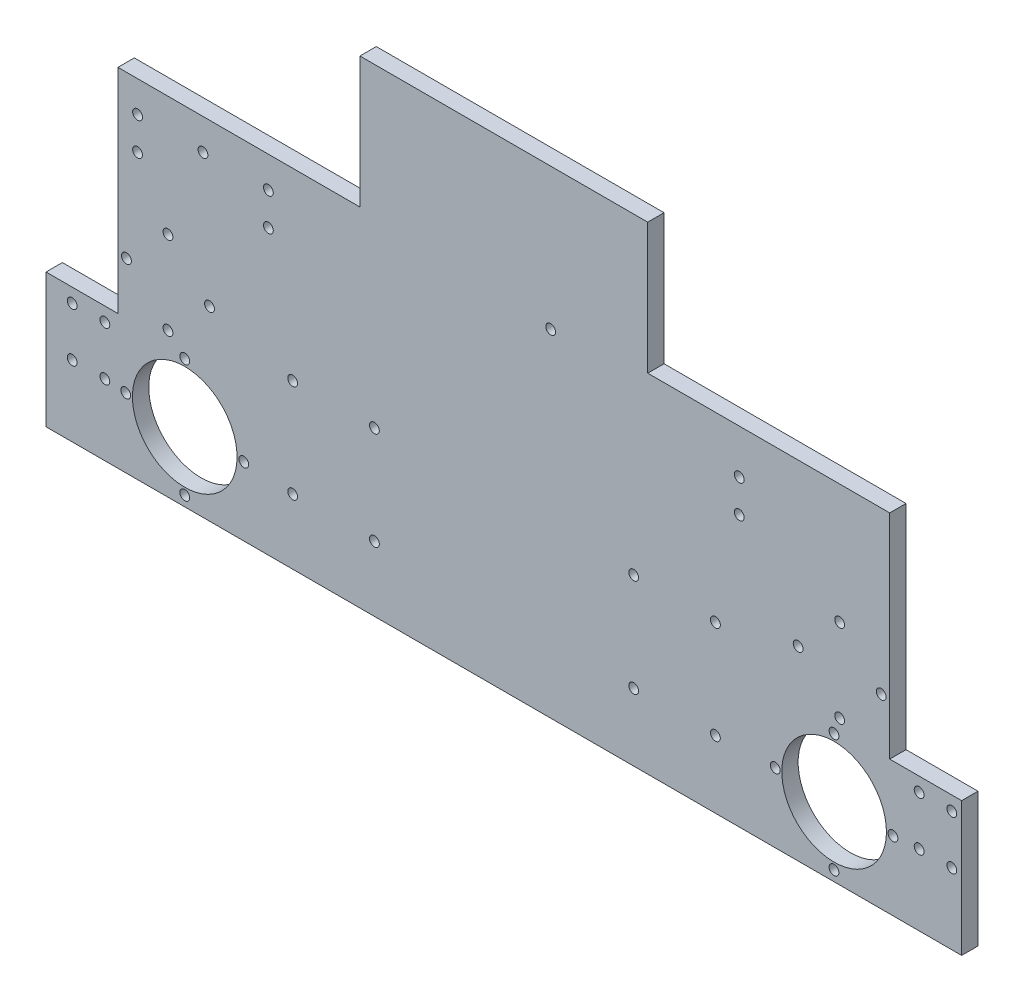
SolidWorks part; units mm, degrees
ref_plane "Front" through (0, 0, 0) normal (0, 0, 1) x (1, 0, 0)
ref_plane "Top" through (0, 0, 0) normal (0, 1, 0) x (1, 0, 0)
ref_plane "Right" through (0, 0, 0) normal (1, 0, 0) x (0, 0, -1)
sketch "Esquisse1" plane through (0, 0, 0) normal (0, 0, 1) x (1, 0, 0)
  line L2 (0, 0) -> (0, 65.2)
  line L3 (74, 138.2) -> (162, 138.2)
  line L4 (236, 0) -> (236, 65.2)
  line L7 (0, 65.2) -> (74, 65.2)
  line L8 (74, 138.2) -> (74, 65.2)
  line L9 (0, 0) -> (-22, 0)
  line L10 (0, 0) -> (0, -37)
  line L11 (236, 65.2) -> (162, 65.2)
  line L12 (162, 138.2) -> (162, 65.2)
  line L14 (0, 0) -> (0, 34)
  line L18 (236, 0) -> (236, 34)
  line L22 (0, 0) -> (0, -37)
  line L23 (0, -37) -> (236, -37)
  line L24 (236, 0) -> (236, -37)
  line L25 (0, -37) -> (-22, -37)
  line L26 (-22, 0) -> (-22, -37)
  line L27 (236, 0) -> (258, 0)
  line L28 (236, 0) -> (236, -37)
  line L29 (236, -37) -> (258, -37)
  line L30 (258, 0) -> (258, -37)
  dimension "D2" = 175.2
  dimension "D3" = 88
  dimension "D4" = 65.2
  dimension "D5" = 65.2
  dimension "D6" = 74
  dimension "D8" = 34
  dimension "D9" = 34
  dimension "D11" = 37
  dimension "D16" = 74
  dimension "D18" = 22
  dimension "D19" = 22
extrude "Boss.-Extru.2" add sketch "Esquisse1" along normal blind 5
sketch "Esquisse2" plane through (0, 0, 5) normal (0, 0, 1) x (1, 0, 0)
  circle A17 centre (26, 55.7) radius 1.5
  circle A21 centre (46, 55.7) radius 1.5
  circle A313 centre (6, 55.7) radius 1.5
  circle A315 centre (6, 45.7) radius 1.5
  circle A321 centre (-4, -4.3) radius 1.5
  circle A323 centre (-14, -4.3) radius 1.5
  circle A393 centre (-4, -19.3) radius 1.5
  circle A395 centre (-14, -19.3) radius 1.5
  point P0 (0, 0)
extrude "Enlèv. mat.-Extru.1" cut sketch "Esquisse2" against normal blind 14
sketch "Esquisse3" plane through (0, 0, 5) normal (0, 0, 1) x (1, 0, 0)
  circle A155 centre (132.3312, 62.0023) radius 1.5
  point P0 (132.3312, 62.0023)
extrude "Enlèv. mat.-Extru.2" cut sketch "Esquisse3" against normal blind 32
sketch "Esquisse4" plane through (0, 0, 0) normal (0, 0, -1) x (-1, 0, 0)
  circle A0 centre (-190, 51.7) radius 1.5
  circle A1 centre (-190, 41.7) radius 1.5
  dimension "D1" = 3
  dimension "D2" = 3
extrude "Enlèv. mat.-Extru.3" cut sketch "Esquisse4" against normal through all
sketch "Esquisse5" plane through (0, 0, 5) normal (0, 0, 1) x (1, 0, 0)
  circle A0 centre (46, 45.7) radius 1.5006
  dimension "D1" = 3.0012
extrude "Enlèv. mat.-Extru.4" cut sketch "Esquisse5" against normal through all
sketch "Esquisse6" plane through (0, 0, 5) normal (0, 0, 1) x (1, 0, 0)
  circle A0 centre (245, -4.3) radius 1.5
  circle A1 centre (255, -4.3) radius 1.5
  circle A2 centre (255, -19.3) radius 1.5
  circle A3 centre (245, -19.3) radius 1.5
  dimension "D1" = 3
  dimension "D2" = 3
  dimension "D3" = 3
  dimension "D4" = 3
extrude "Enlèv. mat.-Extru.5" cut sketch "Esquisse6" against normal through all
sketch "Esquisse7" plane through (0, 0, 0) normal (0, 0, -1) x (-1, 0, 0)
  circle A0 centre (-15.3, 28.6) radius 1.5
  circle A1 centre (-2.6, 15.9) radius 1.5
  circle A2 centre (-15.3, 3.2) radius 1.5
  circle A3 centre (-28, 15.9) radius 1.5
  circle A4 centre (-208, 15.9) radius 1.5
  circle A5 centre (-220.7, 3.2) radius 1.5
  circle A6 centre (-233.4, 15.9) radius 1.5
  circle A7 centre (-220.7, 28.6) radius 1.5
  dimension "D1" = 3
  dimension "D2" = 3
  dimension "D3" = 3
  dimension "D4" = 3
  dimension "D5" = 3
  dimension "D6" = 3
  dimension "D7" = 3
  dimension "D8" = 3
extrude "Enlèv. mat.-Extru.6" cut sketch "Esquisse7" against normal through all
sketch "Esquisse8" plane through (0, 0, 5) normal (0, 0, 1) x (1, 0, 0)
  line L0 (162, 138.2) -> (162, 65.2) construction
  line L1 (74, 138.2) -> (162, 138.2)
  line L2 (74, 138.2) -> (74, 105.2)
  line L3 (74, 105.2) -> (162, 105.2)
  line L4 (162, 138.2) -> (162, 105.2)
  dimension "D1" = 33
extrude "Enlèv. mat.-Extru.7" cut sketch "Esquisse8" against normal through all
sketch "Esquisse9" plane through (0, 0, 5) normal (0, 0, 1) x (1, 0, 0)
  circle A0 centre (182.7, -20.4) radius 1.5
  circle A1 centre (157.7, -20.4) radius 1.5
  circle A2 centre (157.7, 9.6) radius 1.5
  circle A3 centre (182.7, 9.6) radius 1.5074
  circle A4 centre (78.4242, -21.0951) radius 1.5
  circle A5 centre (53.4242, -21.0951) radius 1.5
  circle A6 centre (78.4242, 8.9049) radius 1.5
  circle A7 centre (53.4242, 8.9049) radius 1.5
  dimension "D1" = 3
  dimension "D2" = 3
  dimension "D3" = 3
  dimension "D4" = 3
  dimension "D5" = 3
  dimension "D6" = 3
  dimension "D7" = 3
  dimension "D8" = 3.0147
extrude "Enlèv. mat.-Extru.8" cut sketch "Esquisse9" against normal through all
sketch "Esquisse10" plane through (0, 0, 5) normal (0, 0, 1) x (1, 0, 0)
  line L1 (-22, -37) -> (258, -37)
  line L2 (-22, -37) -> (-22, -41)
  line L3 (-22, -41) -> (258, -41)
  line L4 (258, -37) -> (258, -41)
  dimension "D1" = 4
extrude "Boss.-Extru.3" add sketch "Esquisse10" against normal blind 5
sketch "Esquisse12" plane through (0, 0, 5) normal (0, 0, 1) x (1, 0, 0)
  circle A0 centre (20.4242, -19.8) radius 16
  circle A1 centre (219, -19.8) radius 16
  dimension "D1" = 32
  dimension "D2" = 32
extrude "Enlèv. mat.-Extru.10" cut sketch "Esquisse12" against normal through all
sketch "Esquisse13" plane through (0, 0, 5) normal (0, 0, 1) x (1, 0, 0)
  circle A0 centre (2.3835, -19.8) radius 1.5
  circle A1 centre (20.4242, -1.7412) radius 1.5
  circle A2 centre (38.4788, -20.0401) radius 1.5
  circle A3 centre (20.4242, -37.8708) radius 1.5
  circle A4 centre (218.9653, -1.7412) radius 1.5
  circle A5 centre (236.9863, -19.8) radius 1.5
  circle A6 centre (200.9946, -19.8) radius 1.5
  circle A7 centre (218.9653, -37.8708) radius 1.5
  point P16 (219, -1.3479)
  point P17 (218.9653, -1.6077)
  point P18 (0, 0)
  point P19 (218.9653, -1.7412)
  point P20 (236.9863, -19.8)
  point P21 (218.9653, -37.8708)
  point P22 (200.9946, -19.8)
  point P23 (2.3835, -19.8)
  point P24 (38.4788, -20.0401)
  point P25 (20.4242, -37.8708)
  point P26 (20.4242, -1.7412)
  dimension "D1" = 3
  dimension "D2" = 3
  dimension "D3" = 3
  dimension "D4" = 3
  dimension "D5" = 3
  dimension "D6" = 3
  dimension "D7" = 3
  dimension "D8" = 3
extrude "Enlèv. mat.-Extru.11" cut sketch "Esquisse13" against normal through all
